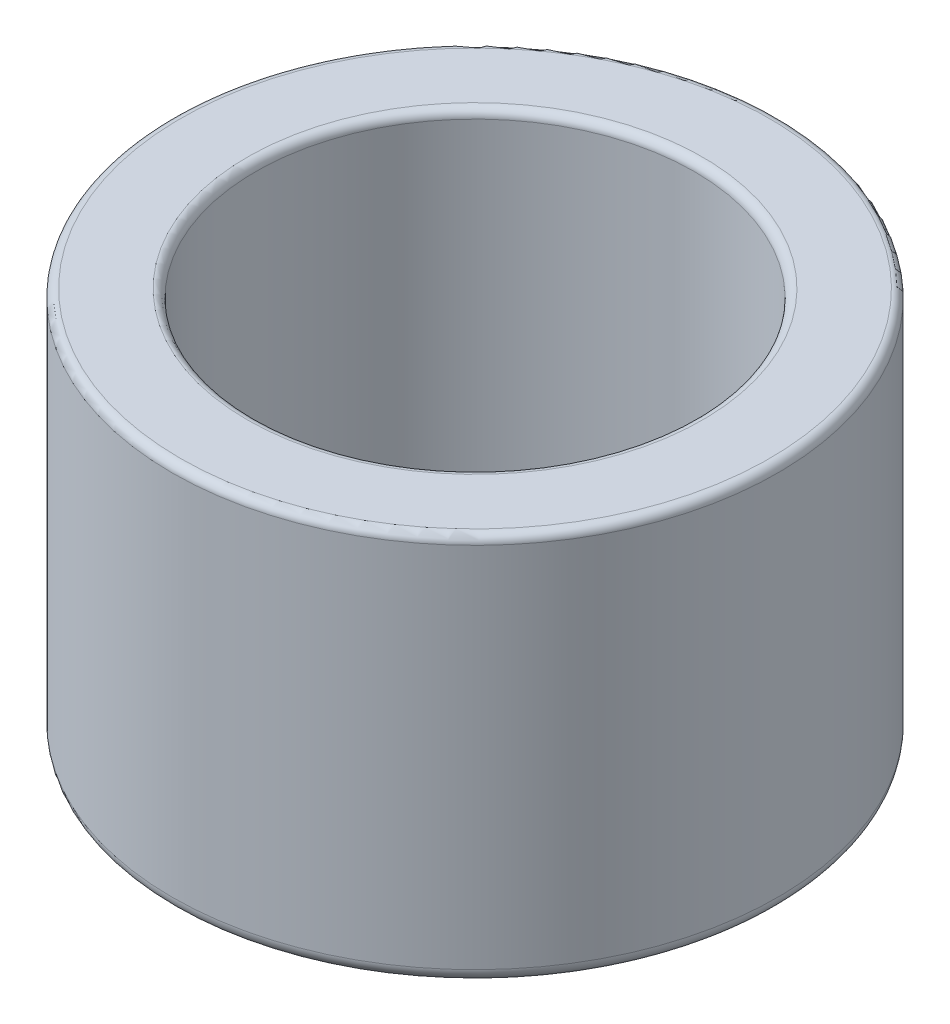
SolidWorks part; units mm, degrees
ref_plane "Front Plane" through (0, 0, 0) normal (0, 0, 1) x (1, 0, 0)
ref_plane "Top Plane" through (0, 0, 0) normal (0, 1, 0) x (1, 0, 0)
ref_plane "Right Plane" through (0, 0, 0) normal (1, 0, 0) x (0, 0, -1)
sketch "Sketch1" plane through (0, 0, 0) normal (0, 1, 0) x (1, 0, 0)
  circle A0 centre (0, 0) radius 7.8782
  circle A1 centre (0, 0) radius 10.8782
  dimension "D1" = 15.7563
  dimension "D2" = 3
extrude "Boss-Extrude1" add sketch "Sketch1" along normal blind 14
fillet "Fillet1" radius 0.3 1 edges at (0, 14, 10.8782)
fillet "Fillet5" radius 0.3 1 edges at (0, 14, 7.8782)
fillet "Fillet6" radius 0.5 1 edges at (0, 0, 10.8782)
fillet "Fillet7" radius 0.5 1 edges at (0, 0, 7.8782)
